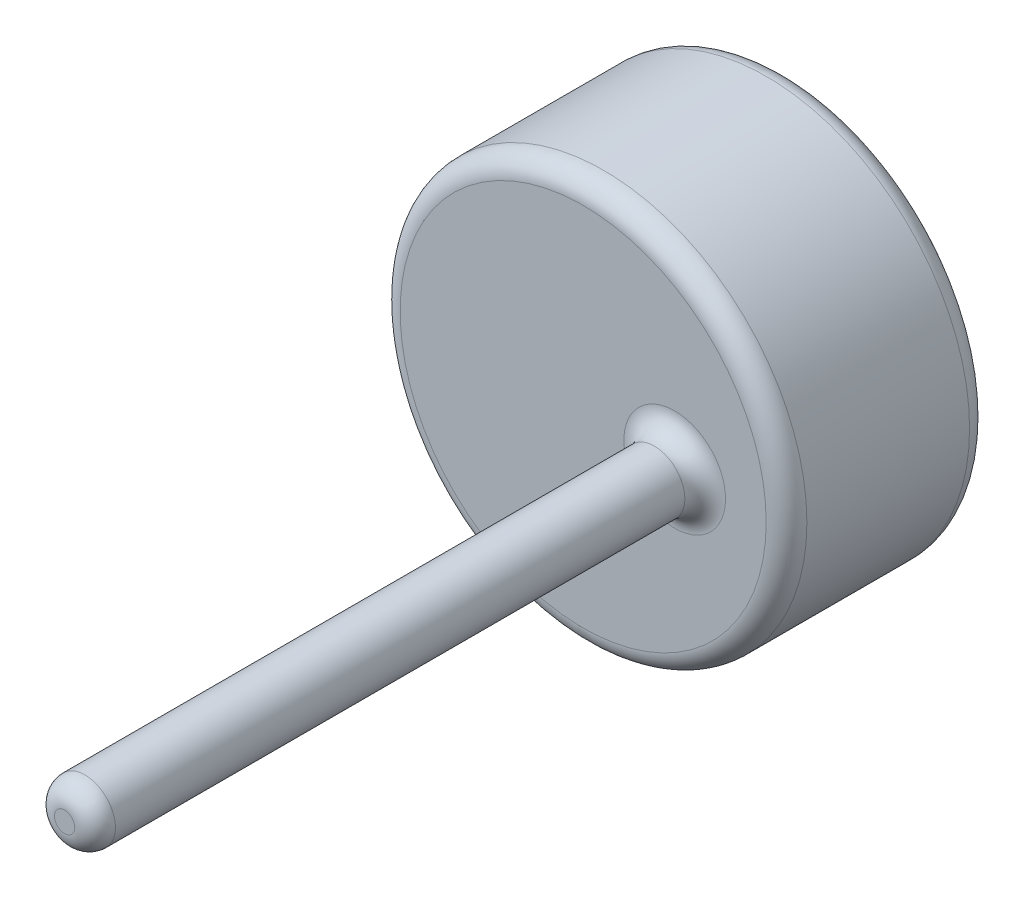
SolidWorks part; units mm, degrees
ref_plane "Front Plane" through (0, 0, 0) normal (0, 0, 1) x (1, 0, 0)
ref_plane "Top Plane" through (0, 0, 0) normal (0, 1, 0) x (1, 0, 0)
ref_plane "Right Plane" through (0, 0, 0) normal (1, 0, 0) x (0, 0, -1)
sketch "Sketch1" plane through (0, 0, 0) normal (0, 0, 1) x (1, 0, 0)
  circle A0 centre (0, 0) radius 10
  dimension "D1" = 20
extrude "Boss-Extrude1" add sketch "Sketch1" along normal blind 10
sketch "Sketch2" plane through (0, 0, 10) normal (0, 0, 1) x (1, 0, 0)
  circle A0 centre (4.5, 0) radius 1.5
  dimension "D1" = 3
  dimension "D2" = 4.5
extrude "Boss-Extrude2" add sketch "Sketch2" along normal blind 30
fillet "Fillet1" radius 1 4 edges at (6, 0, 40) (10, 0, 10) (6, 0, 10) (10, 0, 0)
